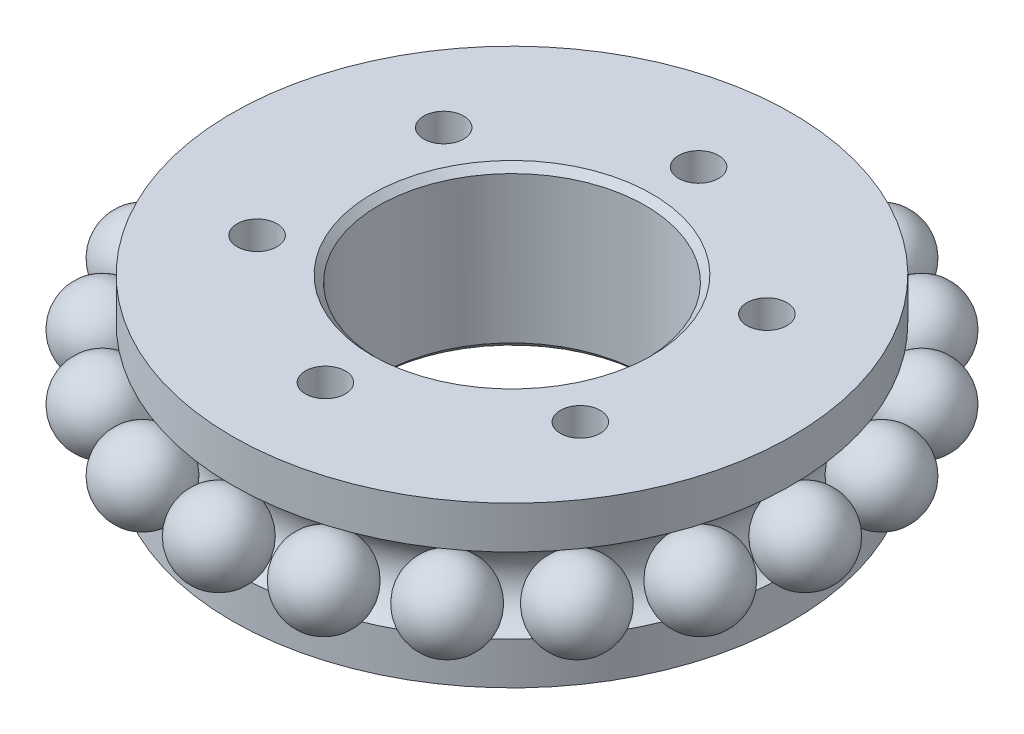
SolidWorks part; units mm, degrees
material "合金钢"
ref_plane "前视基准面" through (0, 0, 0) normal (0, 0, 1) x (1, 0, 0)
ref_plane "上视基准面" through (0, 0, 0) normal (0, 1, 0) x (1, 0, 0)
ref_plane "右视基准面" through (0, 0, 0) normal (1, 0, 0) x (0, 0, -1)
sketch "草图1" plane through (0, 0, 0) normal (0, 0, 1) x (1, 0, 0)
  line L0 (0, 41.0991) -> (0, -42.454) construction
  line L1 (-46.9153, 0) -> (60.5747, 0) construction
  line L2 (-10, -6) -> (-10, 6)
  line L3 (-10, 6) -> (-21, 6)
  line L4 (-21, 6) -> (-21, 2.8284)
  line L5 (0, -41.0991) -> (0, 42.454) construction
  line L6 (-21, -6) -> (-21, -2.8284)
  line L7 (-10, -6) -> (-21, -6)
  arc A0 (-21, 2.8284) -> (-21, -2.8284) centre (-22, 0) cw
  point P15 (-10, 0)
  dimension "D1" = 3
  dimension "D2" = 11
  dimension "D3" = 10
  dimension "D4" = 12
  dimension "D5" = 1
revolve "旋转1" add sketch "草图1" angle 360 about L0
sketch "草图2" plane through (0, 0, 0) normal (1, 0, 0) x (0, 0, -1)
  line L1 (-21, 6) -> (-21, 2.8284) construction
  line L2 (-22, 0) -> (-22, -7.0156) construction
  line L3 (-22, 0) -> (-22, 6.2742) construction
  line L4 (-22, 3) -> (-22, -3)
  arc A0 (-22, -3) -> (-22, 3) centre (-22, 0) ccw
  dimension "D1" = 6
  dimension "D2" = 1
revolve "旋转4" add sketch "草图2" angle 360 about L4
pattern_circular "阵列(圆周)4" count 20 every 18 about axis through (0, 0, 0) along (0, 1, 0) of bodies 103
sketch "草图3" plane through (0, 6, 0) normal (0, 1, 0) x (1, 0, 0)
  circle A0 centre (0, 0) radius 14 construction
  circle A1 centre (0, 14) radius 1.5
  circle A2 centre (12.1244, 7) radius 1.5
  circle A3 centre (12.1244, -7) radius 1.5
  circle A4 centre (0, -14) radius 1.5
  circle A5 centre (-12.1244, -7) radius 1.5
  circle A6 centre (-12.1244, 7) radius 1.5
  point P18 (0, 0)
  dimension "D1" = 28
  dimension "D2" = 3
  dimension "D3" = 6
extrude "切除-拉伸1" cut sketch "草图3" against normal blind 20
chamfer "倒角1" distance 0.5 angle 45 2 edges at (0, -6, 10) (0, 6, 10)
